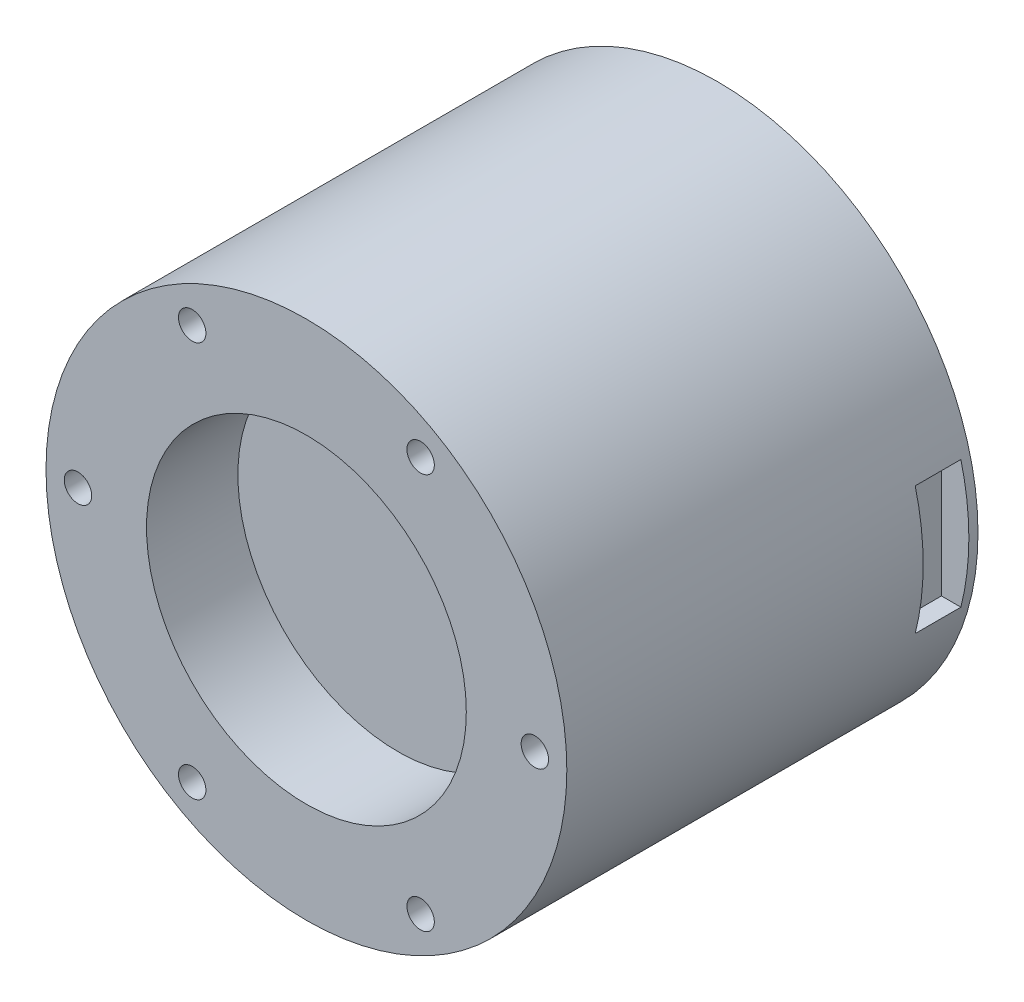
SolidWorks part; units mm, degrees
ref_plane "前视基准面" through (0, 0, 0) normal (0, 0, 1) x (1, 0, 0)
ref_plane "上视基准面" through (0, 0, 0) normal (0, 1, 0) x (1, 0, 0)
ref_plane "右视基准面" through (0, 0, 0) normal (1, 0, 0) x (0, 0, -1)
other "Configuration Table"
sketch "草图1" plane through (0, 0, 0) normal (0, 0, 1) x (1, 0, 0)
  circle A0 centre (0, 0) radius 28.5
  dimension "D1" = 57
extrude "凸台-拉伸1" add sketch "草图1" along normal blind 45
sketch "草图2" plane through (0, 0, 45) normal (0, 0, 1) x (1, 0, 0)
  circle A0 centre (25, 0) radius 1.5
  dimension "D1" = 3
  dimension "D2" = 25
extrude "切除-拉伸1" cut sketch "草图2" against normal blind 5
pattern_circular "阵列(圆周)1" count 6 over 360 about axis through (0, 0, 0) along (0, 0, 1) of "切除-拉伸1"
sketch "草图3" plane through (0, 0, 45) normal (0, 0, 1) x (1, 0, 0)
  circle A0 centre (0, 0) radius 17.5
  dimension "D1" = 35
extrude "切除-拉伸2" cut sketch "草图3" against normal blind 10
sketch "草图4" plane through (0, 0, 0) normal (0, 0, -1) x (-1, 0, 0)
  line L0 (-33.611, 0) -> (37.9068, 0) construction
  line L1 (0, 35.4194) -> (0, -37.0347) construction
  line L2 (-25.5, -7) -> (-27.6897, -7)
  line L3 (25.5, 7) -> (27.6897, 7)
  line L4 (25.5, 7) -> (25.5, -7)
  line L5 (25.5, -7) -> (27.6897, -7)
  line L7 (25.5, 7) -> (31.5, -7) construction
  line L8 (25.5, -7) -> (31.5, 7) construction
  line L9 (-25.5, 7) -> (-27.6897, 7)
  line L10 (-25.5, 7) -> (-25.5, -7)
  circle A0 centre (0, 0) radius 28.5 construction
  arc A1 (27.6897, 7) -> (27.6897, -7) centre (0, 0) cw
  arc A2 (-27.6897, 7) -> (-27.6897, -7) centre (0, 0) ccw
  point P5 (28.5, 0)
  dimension "D1" = 25.5
  dimension "D2" = 7
extrude "切除-拉伸3" cut sketch "草图4" against normal blind 5 from offset 1 offset against normal yes
sketch "草图5" plane through (0, 0, 0) normal (0, 0, -1) x (-1, 0, 0)
  line L0 (0, 30.1434) -> (0, -31.7185) construction
  line L2 (-4, -25.5) -> (4, -25.5)
  line L3 (-4, -25.5) -> (-4, -28.2179)
  line L5 (4, -25.5) -> (4, -28.2179)
  line L6 (-4, -25.5) -> (4, -34.6238) construction
  line L7 (-4, -34.6238) -> (4, -25.5) construction
  arc A0 (4, -28.2179) -> (-4, -28.2179) centre (0, 0) cw
  circle A1 centre (0, 0) radius 28.5 construction
  point P3 (0, -30.0619)
  dimension "D1" = 25.5
  dimension "D2" = 4
extrude "切除-拉伸4" cut sketch "草图5" against normal blind 8 from offset 1 offset against normal yes
sketch "草图6" plane through (0, 0, 0) normal (0, 0, -1) x (-1, 0, 0)
  line L0 (35.9713, 0) -> (-38.3317, 0) construction
  line L1 (0, 0) -> (23.8824, 23.8824) construction
  circle A0 centre (13.435, 13.435) radius 1.5
  dimension "D2" = 3
  dimension "D1" = 45
  dimension "D3" = 19
extrude "切除-拉伸5" cut sketch "草图6" against normal blind 4
pattern_circular "阵列(圆周)2" count 4 over 360 about axis through (0, 0, 0) along (0, 0, 1) of "切除-拉伸5"
